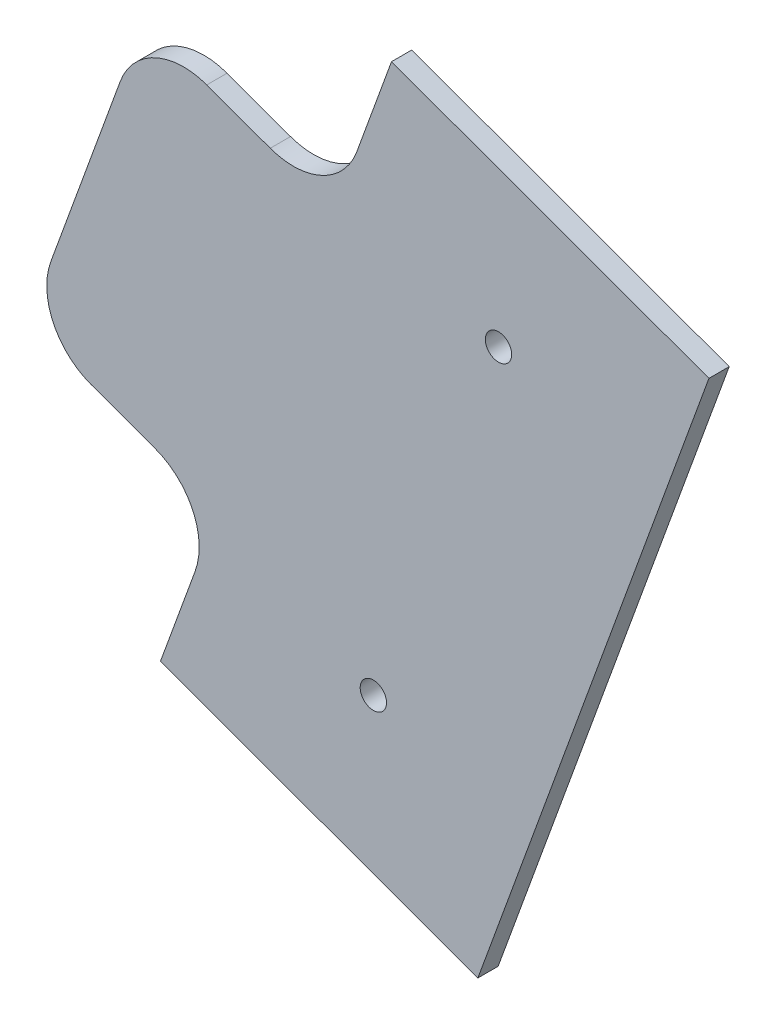
SolidWorks part; units mm, degrees
material "Thornel Mat VMA"
ref_plane "前视基准面" through (0, 0, 0) normal (0, 0, 1) x (1, 0, 0)
ref_plane "上视基准面" through (0, 0, 0) normal (0, 1, 0) x (1, 0, 0)
ref_plane "右视基准面" through (0, 0, 0) normal (1, 0, 0) x (0, 0, -1)
other "Configuration Table"
sketch "草图1" plane through (0, 0, 0) normal (0, 0, 1) x (1, 0, 0)
  line L0 (366.8083, 667.0656) -> (401.0103, 761.0349)
  line L3 (366.8083, 667.0656) -> (319.8237, 684.1666)
  line L4 (319.8237, 684.1666) -> (354.0257, 778.1359)
  line L7 (401.0103, 761.0349) -> (354.0257, 778.1359)
  line L9 (328.5815, 686.2999) -> (326.8714, 681.6014) construction
  dimension "D1" = 100
  dimension "D2" = 50
  dimension "D3" = 7.5
extrude "凸台-拉伸1" add sketch "草图1" along normal blind 3
sketch "草图2" plane through (0, 0, 3) normal (0, 0, 1) x (1, 0, 0)
  line L0 (319.8237, 684.1666) -> (366.8083, 667.0656) construction
  circle A2 centre (351.3382, 695.5761) radius 1.95
  circle A3 centre (369.862, 749.4822) radius 1.95
  dimension "D2" = 3.9
  dimension "D1" = 57
  dimension "D3" = 21.5
extrude "切除-拉伸1" cut sketch "草图2" against normal up to next
sketch "草图3" plane through (0, 0, 3) normal (0, 0, 1) x (1, 0, 0)
  line L0 (345.4752, 754.6435) -> (317.2844, 764.9041)
  line L1 (354.0257, 778.1359) -> (319.8237, 684.1666) construction
  line L2 (317.2844, 764.9041) -> (300.1834, 717.9195)
  line L3 (300.1834, 717.9195) -> (328.3742, 707.6589)
  line L4 (345.4752, 754.6435) -> (328.3742, 707.6589)
  line L5 (401.0103, 761.0349) -> (354.0257, 778.1359) construction
  dimension "D1" = 50
  dimension "D2" = 30
  dimension "D3" = 25
extrude "凸台-拉伸2" add sketch "草图3" against normal blind 3
fillet "圆角1" radius 10 4 edges at (317.2844, 764.9041, 1.5) (300.1834, 717.9195, 1.5) (328.3742, 707.6589, 1.5) (345.4752, 754.6435, 1.5)
